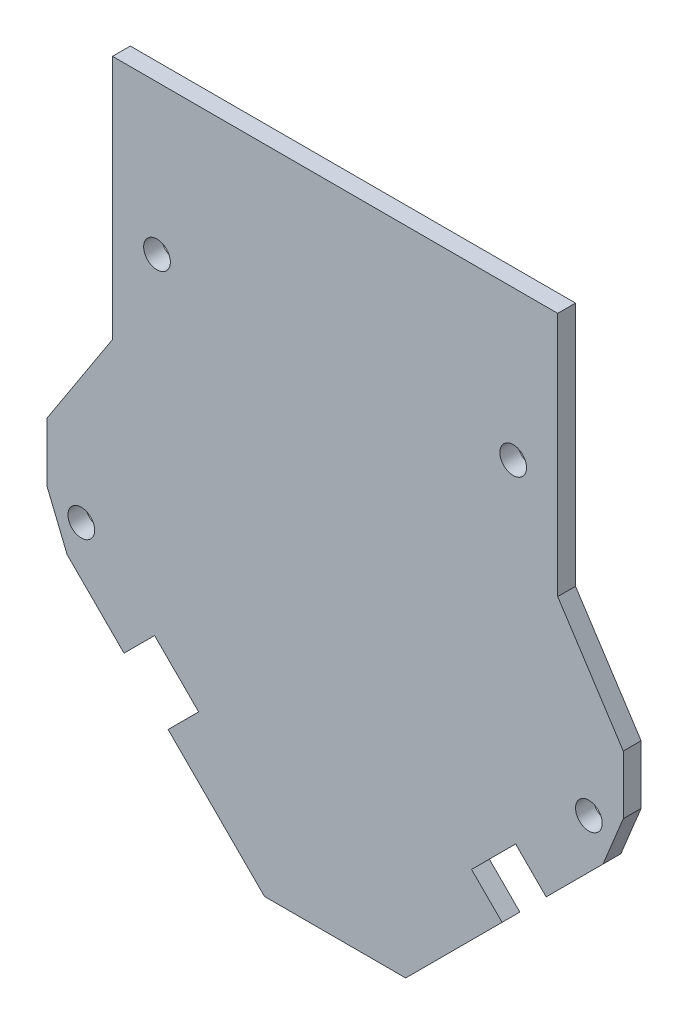
SolidWorks part; units mm, degrees
ref_plane "Front" through (0, 0, 0) normal (0, 0, 1) x (1, 0, 0)
ref_plane "Top" through (0, 0, 0) normal (0, 1, 0) x (1, 0, 0)
ref_plane "Right" through (0, 0, 0) normal (1, 0, 0) x (0, 0, -1)
sketch "Sketch1" plane through (0, 0, 0) normal (0, 0, 1) x (1, 0, 0)
  line L0 (-15, 13.5) -> (-15, 38.5)
  line L1 (15, 13.5) -> (26.8117, -4.6883)
  line L2 (15, -26.5) -> (7.9289, -33.5711)
  line L3 (7.9289, -33.5711) -> (7.9289, -52.5711)
  line L4 (-15, 13.5) -> (-26.8117, -4.6883)
  line L5 (-15, -26.5) -> (-7.9289, -33.5711)
  line L6 (-7.9289, -33.5711) -> (-7.9289, -52.5711)
  line L7 (-7.9289, -52.5711) -> (7.9289, -52.5711)
  line L8 (26.8117, -4.6883) -> (15, -16.5)
  line L9 (15, -16.5) -> (15, -26.5)
  line L10 (-26.8117, -4.6883) -> (-15, -16.5)
  line L11 (-15, -16.5) -> (-15, -26.5)
  line L12 (-15, 38.5) -> (15, 38.5)
  line L13 (15, 38.5) -> (15, 13.5)
  dimension "D1" = 30
  dimension "D2" = 40
  dimension "D3" = 40
  dimension "D4" = 10
  dimension "D5" = 10
  dimension "D6" = 19
  dimension "D7" = 327
  dimension "D8" = 25
  dimension "D9" = 15
  dimension "D10" = 15
  dimension "D11" = 10
  dimension "D12" = 135
  dimension "D13" = 135
  dimension "D14" = 327
  dimension "D15" = 135
  dimension "D16" = 135
extrude "Extrude1" add sketch "Sketch1" along normal blind 2
sketch "Sketch4" plane through (0, 0, 2) normal (0, 0, 1) x (1, 0, 0)
  line L0 (-26.8117, -4.6883) -> (-32.3637, -6.9632)
  line L1 (-32.3637, -6.9632) -> (-30.0888, -12.5152)
  line L2 (-30.0888, -12.5152) -> (-22.2121, -9.2879)
  line L3 (-26.8117, -4.6883) -> (-15, -16.5) construction
  line L4 (-22.2121, -9.2879) -> (-26.8117, -4.6883)
  circle A0 centre (-28.5, -8.6) radius 1.5
  dimension "D3" = 3
  dimension "D1" = 6
  dimension "D2" = 6
  dimension "D4" = 28.5
  dimension "D5" = 8.6
extrude "Extrude3" add sketch "Sketch4" against normal up to surface (2 mm away) up to face at (0, -11.6901, 0)
mirror "Mirror1" about plane through (0, 0, 0) normal (1, 0, 0) of "Extrude3"
sketch "Sketch6" plane through (0, 0, 2) normal (0, 0, 1) x (1, 0, 0)
  line L0 (0, -44.5711) -> (-7.9289, -44.5711)
  line L1 (-7.9289, -33.5711) -> (-7.9289, -52.5711) construction
  line L2 (-7.9289, -44.5711) -> (-18, -54.6421)
  line L3 (-18, -54.6421) -> (18, -54.6421)
  line L4 (18, -54.6421) -> (7.9289, -44.5711)
  line L5 (7.9289, -44.5711) -> (0, -44.5711)
  line L6 (7.9289, -52.5711) -> (7.9289, -33.5711) construction
  line L7 (-7.9289, -52.5711) -> (7.9289, -52.5711) construction
  dimension "D1" = 45
  dimension "D2" = 36
  dimension "D3" = 8
extrude "Extrude5" add sketch "Sketch6" against normal up to surface (2 mm away) up to face at (0, -11.0597, 0)
fillet "Fillet2" radius 3 2 edges at (18, -54.6421, 1) (-18, -54.6421, 1)
sketch "Sketch7" plane through (0, 0, 2) normal (0, 0, 1) x (1, 0, 0)
  line L0 (-10.7574, -54.6421) -> (10.7574, -54.6421) construction
  circle A0 centre (-11, -52.0021) radius 1.5
  dimension "D3" = 3
  dimension "D1" = 2.64
  dimension "D2" = 11
extrude "Extrude6" cut sketch "Sketch7" against normal up to surface (2 mm away) up to face at (0, -17.289, 0)
mirror "Mirror4" about plane through (0, 0, 0) normal (1, 0, 0) of "Extrude6"
sketch "Sketch8" plane through (0, 0, 2) normal (0, 0, 1) x (1, 0, 0)
  line L0 (-26.8117, -4.6883) -> (-32.3637, -6.9632)
  line L1 (-26.8117, -4.6883) -> (-15, 13.5)
  line L2 (-15, 26.3525) -> (-15, 13.5)
  line L3 (-15, 26.3525) -> (-32.3637, -0.3852)
  line L4 (-32.3637, -0.3852) -> (-32.3637, -6.9632)
  dimension "D1" = 7
extrude "Extrude7" add sketch "Sketch8" against normal up to surface (2 mm away) up to face at (30, -8.6, 0)
sketch "Sketch9" plane through (0, 0, 2) normal (0, 0, 1) x (1, 0, 0)
  line L0 (-22.2121, -9.2879) -> (-25.2217, -10.521)
  line L1 (-30.0888, -12.5152) -> (-22.2121, -9.2879) construction
  line L2 (-25.2217, -10.521) -> (-15, -20.7426)
  line L3 (-15, -16.5) -> (-15, -26.5) construction
  line L4 (-15, -20.7426) -> (-15, -16.5)
  line L5 (-15, -16.5) -> (-22.2121, -9.2879)
  dimension "D1" = 3
extrude "Extrude8" add sketch "Sketch9" against normal up to surface (2 mm away) up to face at (30, -8.6, 0)
sketch "Sketch10" plane through (0, 0, 2) normal (0, 0, 1) x (1, 0, 0)
  line L0 (-25.2217, -10.521) -> (-30.0888, -12.5152)
  line L1 (-30.0888, -12.5152) -> (-23.7026, -18.9014)
  line L2 (-23.7026, -18.9014) -> (-20.2719, -15.4707)
  line L3 (-25.2217, -10.521) -> (-15, -20.7426) construction
  line L4 (-25.2217, -10.521) -> (-20.2719, -15.4707)
  dimension "D1" = 7
extrude "Extrude9" add sketch "Sketch10" against normal up to surface (2 mm away) up to face at (-0.3567, -16.8024, 0)
sketch "Sketch11" plane through (0, 0, 2) normal (0, 0, 1) x (1, 0, 0)
  line L0 (-15.3222, -20.4205) -> (-18.7529, -23.8512)
  line L1 (-20.2719, -15.4707) -> (-15, -20.7426) construction
  line L2 (-18.7529, -23.8512) -> (-7.9289, -34.6751)
  line L3 (-30.0888, -12.5152) -> (-23.7026, -18.9014) construction
  line L4 (-15, -26.5) -> (-15, -20.7426)
  line L5 (-15, -20.7426) -> (-15.3222, -20.4205)
  line L6 (-23.7026, -18.9014) -> (-20.2719, -15.4707) construction
  line L8 (-7.9289, -33.5711) -> (-7.9289, -44.5711) construction
  line L9 (-7.9289, -34.6751) -> (-7.9289, -33.5711)
  line L10 (-7.9289, -33.5711) -> (-15, -26.5)
  dimension "D1" = 7
extrude "Extrude10" add sketch "Sketch11" against normal up to surface (2 mm away) up to face at (-1.0926, -17.0843, 0)
sketch "Sketch12" plane through (0, 0, 2) normal (0, 0, 1) x (1, 0, 0)
  line L0 (-25, 10.9539) -> (-25, 38.5)
  line L1 (-15, 26.3525) -> (-32.3637, -0.3852) construction
  line L2 (-25, 38.5) -> (-15, 38.5)
  line L3 (-15, 38.5) -> (-15, 26.3525)
  line L4 (-15, 26.3525) -> (-25, 10.9539)
  dimension "D1" = 10
extrude "Extrude11" add sketch "Sketch12" against normal up to surface (2 mm away) up to face at (-1.2556, -17.0096, 0)
mirror "Mirror5" about plane through (0, 0, 0) normal (1, 0, 0) of "Extrude9", "Extrude7", "Extrude8", "Extrude10"
mirror "Mirror6" about plane through (0, 0, 0) normal (1, 0, 0) of "Extrude11"
sketch "Sketch13" plane through (0, 0, 0) normal (0, 0, -1) x (-1, 0, 0)
  line L1 (-25.1343, -34.6751) -> (27.3105, -34.6751)
  line L2 (-25.1343, -34.6751) -> (-25.1343, -59.1014)
  line L3 (-25.1343, -59.1014) -> (27.3105, -59.1014)
  line L4 (27.3105, -34.6751) -> (27.3105, -59.1014)
extrude "Extrude12" cut sketch "Sketch13" against normal up to surface (2 mm away) up to face at (0, -17.9363, 2)
sketch "Sketch14" plane through (0, 0, 2) normal (0, 0, 1) x (1, 0, 0)
  circle A0 centre (-20, 21.73) radius 1.5
  circle A1 centre (-28.5, -8.6) radius 1.5 construction
  circle A2 centre (20, 21.73) radius 1.5
  circle A3 centre (28.5, -8.6) radius 1.5 construction
  dimension "D1" = 8.5
  dimension "D2" = 30.33
  dimension "D3" = 3
  dimension "D4" = 3
  dimension "D5" = 8.5
extrude "Extrude13" cut sketch "Sketch14" against normal up to surface (2 mm away) up to face at (0, -8.3729, 0)
